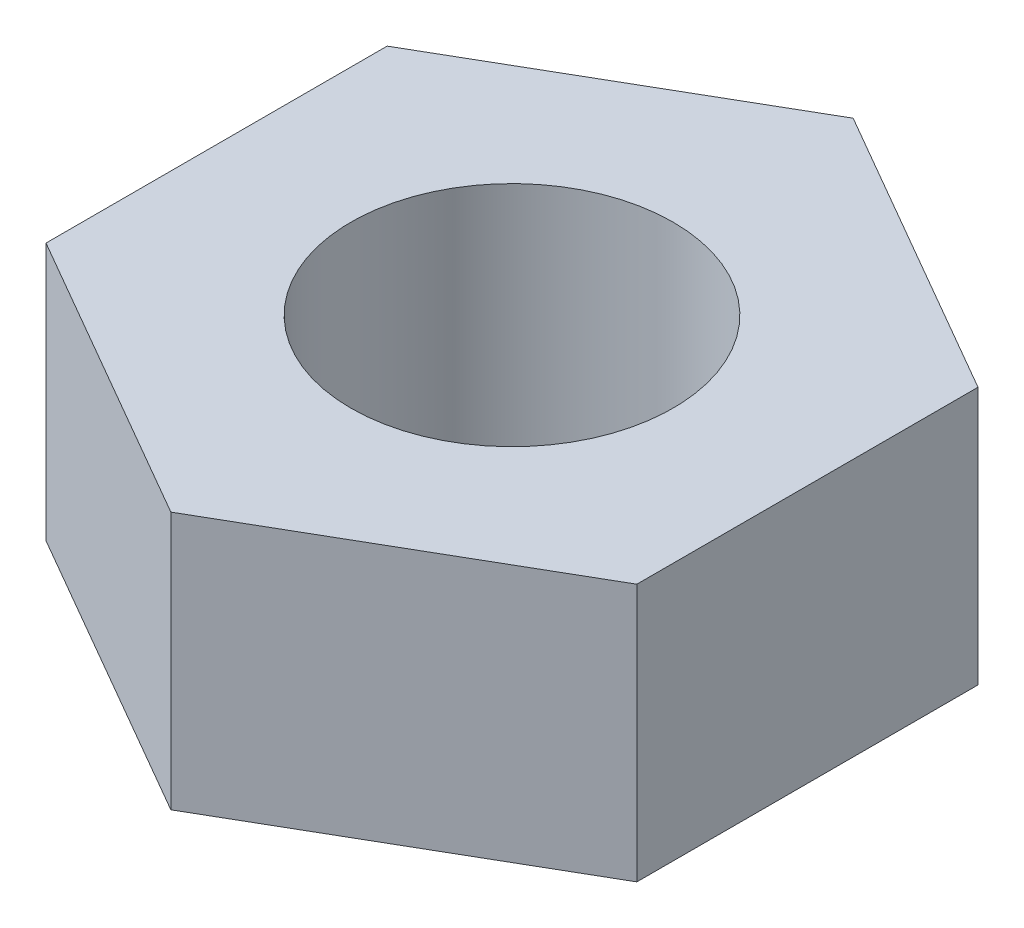
SolidWorks part; units mm, degrees
material "AISI 1045 Сталь, холоднотянутая"
ref_plane "Спереди" through (0, 0, 0) normal (0, 0, 1) x (1, 0, 0)
ref_plane "Сверху" through (0, 0, 0) normal (0, 1, 0) x (1, 0, 0)
ref_plane "Справа" through (0, 0, 0) normal (1, 0, 0) x (0, 0, -1)
sketch "Эскиз1" plane through (0, 0, 0) normal (0, 1, 0) x (1, 0, 0)
  line L1 (0, 3.1754) -> (-2.75, 1.5877)
  line L2 (-2.75, 1.5877) -> (-2.75, -1.5877)
  line L3 (-2.75, -1.5877) -> (0, -3.1754)
  line L4 (0, -3.1754) -> (2.75, -1.5877)
  line L5 (2.75, -1.5877) -> (2.75, 1.5877)
  line L6 (2.75, 1.5877) -> (0, 3.1754)
  circle A0 centre (0, 0) radius 2.75 construction
  circle A1 centre (0, 0) radius 1.5
  dimension "D1" = 5.5
  dimension "D2" = 3
extrude "Бобышка-Вытянуть1" add sketch "Эскиз1" along normal blind 2.4
